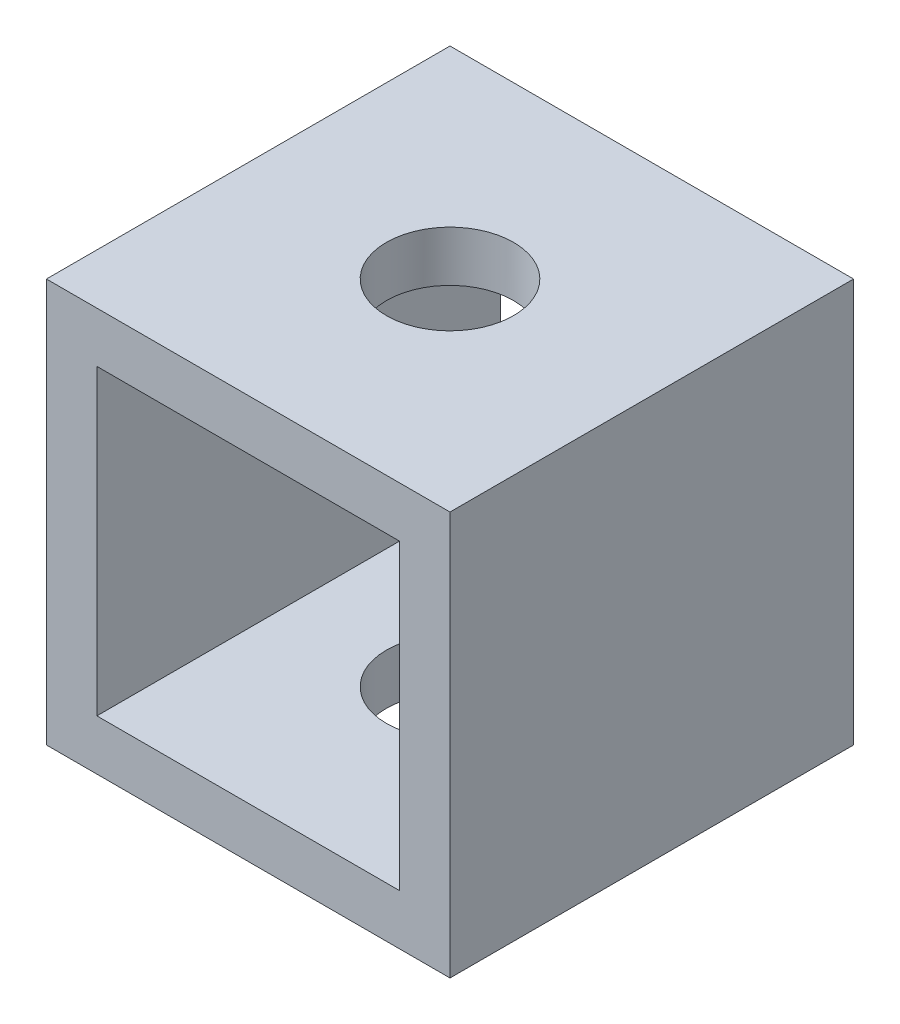
SolidWorks part; units mm, degrees
ref_plane "Front" through (0, 0, 0) normal (0, 0, 1) x (1, 0, 0)
ref_plane "Top" through (0, 0, 0) normal (0, 1, 0) x (1, 0, 0)
ref_plane "Right" through (0, 0, 0) normal (1, 0, 0) x (0, 0, -1)
sketch "Sketch1" plane through (0, 0, 0) normal (0, 0, 1) x (1, 0, 0)
  line L1 (0, 0) -> (-25.4, 0)
  line L2 (0, 0) -> (0, 25.4)
  line L3 (0, 25.4) -> (-25.4, 25.4)
  line L4 (-25.4, 0) -> (-25.4, 25.4)
  line L5 (-22.225, 22.225) -> (-3.175, 22.225)
  line L6 (-22.225, 22.225) -> (-22.225, 3.175)
  line L7 (-22.225, 3.175) -> (-3.175, 3.175)
  line L8 (-3.175, 22.225) -> (-3.175, 3.175)
  dimension "D1" = 25.4
  dimension "D2" = 25.4
  dimension "D3" = 3.175
  dimension "D4" = 3.175
  dimension "D5" = 3.175
  dimension "D6" = 3.175
extrude "Boss-Extrude1" add sketch "Sketch1" along normal blind 25.4
sketch "Sketch3" plane through (0, 25.4, 0) normal (0, 1, 0) x (1, 0, 0)
  line L0 (0, -25.4) -> (0, 0) construction
  line L1 (0, -25.4) -> (-25.4, -25.4) construction
  circle A0 centre (-12.7, -12.7) radius 4
  dimension "D1" = 12.7
  dimension "D2" = 12.7
  dimension "D3" = 8
extrude "Cut-Extrude2" cut sketch "Sketch3" against normal through all
